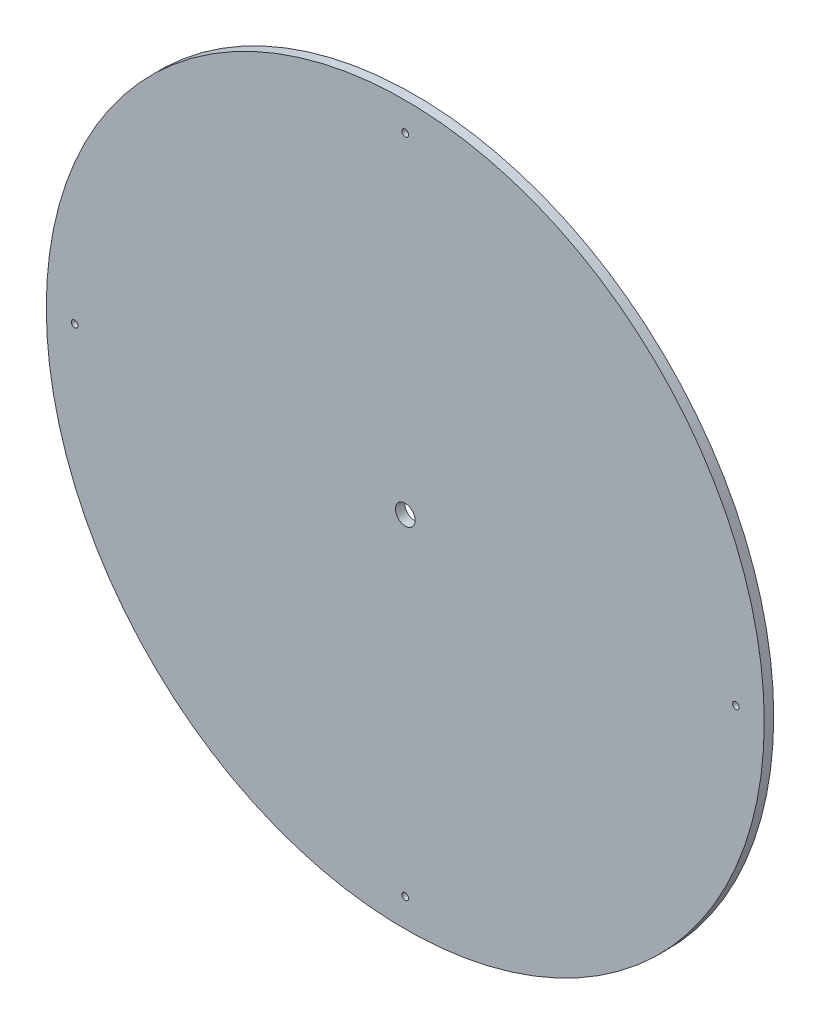
SolidWorks part; units mm, degrees
material "PE 1000 (Yeşil)"
ref_plane "Ön Düzlem" through (0, 0, 0) normal (0, 0, 1) x (1, 0, 0)
ref_plane "Üst Düzlem" through (0, 0, 0) normal (0, 1, 0) x (1, 0, 0)
ref_plane "Sağ Düzlem" through (0, 0, 0) normal (1, 0, 0) x (0, 0, -1)
sketch "Çizim1" plane through (0, 0, 0) normal (0, 0, 1) x (1, 0, 0)
  circle A0 centre (0, 0) radius 455
  dimension "D1" = 910
extrude "Yükseklik-Ekstrüzyon1" add sketch "Çizim1" along normal blind 12
sketch "Çizim2" plane through (0, 0, 12) normal (0, 0, 1) x (1, 0, 0)
  circle A0 centre (0, 0) radius 12.5
  dimension "D1" = 25
extrude "Kes-Ekstrüzyon1" cut sketch "Çizim2" against normal through all
hole_wizard "Ø8.5 (8.5) Çap Delik1" positions "Çizim3" profile "Çizim4" hole size "Ø8.5" standard "DIN" end condition through all
sketch "Çizim3" plane through (0, 0, 12) normal (0, 0, 1) x (1, 0, 0)
  line L6 (0, 419) -> (0, -419) construction
  line L8 (-419, 0) -> (419, 0) construction
  circle A0 centre (0, 0) radius 419 construction
  circle A1 centre (0, 0) radius 419 construction
  circle A2 centre (0, 0) radius 419 construction
  circle A3 centre (0, 0) radius 419 construction
  point P0 (0, 419)
  point P12 (419, 0)
  point P14 (0, -419)
  point P16 (-419, 0)
  dimension "D1" = 838
  dimension "D2" = 4
sketch "Çizim4" plane through (0, 419, 12) normal (1, 0, 0) x (0, -1, 0)
  line L0 (0, 0) -> (0, 12)
  line L1 (0, 12) -> (4.25, 12)
  line L2 (4.25, 12) -> (4.25, 0)
  line L5 (4.25, 0) -> (0, 0)
  line L11 (0, -6.35) -> (0, 107.95) construction
  dimension "Thru Hole Dia." = 8.5
  dimension "Thru Hole Depth" = 12
